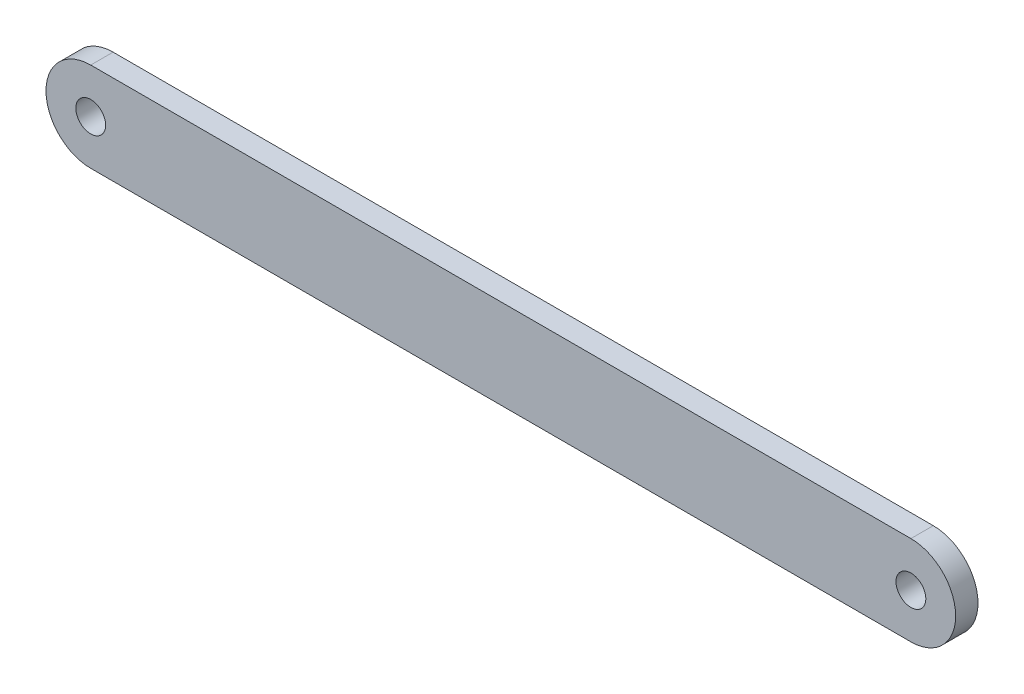
SolidWorks part; units mm, degrees
ref_plane "Front Plane" through (0, 0, 0) normal (0, 0, 1) x (1, 0, 0)
ref_plane "Top Plane" through (0, 0, 0) normal (0, 1, 0) x (1, 0, 0)
ref_plane "Right Plane" through (0, 0, 0) normal (1, 0, 0) x (0, 0, -1)
sketch "Sketch1" plane through (0, 0, 0) normal (0, 0, 1) x (1, 0, 0)
  line L0 (-35.3127, 0) -> (74.6873, 0) construction
  line L1 (-35.3127, 6) -> (74.6873, 6)
  line L2 (-35.3127, -6) -> (74.6873, -6)
  arc A0 (-35.3127, 6) -> (-35.3127, -6) centre (-35.3127, 0) ccw
  arc A1 (74.6873, -6) -> (74.6873, 6) centre (74.6873, 0) ccw
  circle A2 centre (-35.3127, 0) radius 2
  circle A3 centre (74.6873, 0) radius 2
  point P3 (19.6873, 0)
  dimension "D3" = 4
  dimension "D4" = 4
  dimension "D1" = 110
  dimension "D2" = 12
extrude "Boss-Extrude3" add sketch "Sketch1" along normal blind 3
